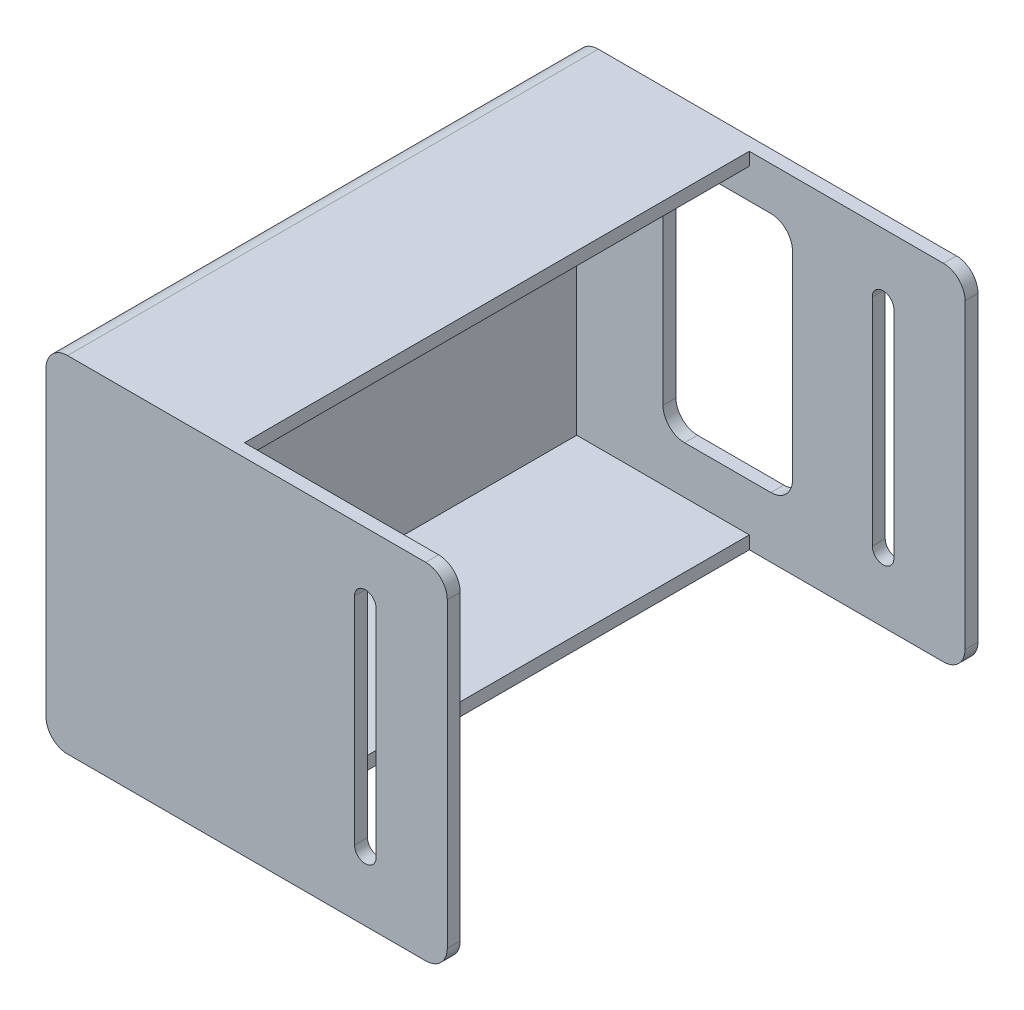
SolidWorks part; units mm, degrees
ref_plane "前基準面" through (0, 0, 0) normal (0, 0, 1) x (1, 0, 0)
ref_plane "上基準面" through (0, 0, 0) normal (0, 1, 0) x (1, 0, 0)
ref_plane "右基準面" through (0, 0, 0) normal (1, 0, 0) x (0, 0, -1)
sketch "草圖1" plane through (0, 0, 0) normal (1, 0, 0) x (0, 0, -1)
  line L1 (-61.5, -40) -> (61.5, -40)
  line L2 (-61.5, -40) -> (-61.5, 40)
  line L3 (-61.5, 40) -> (61.5, 40)
  line L4 (61.5, -40) -> (61.5, 40)
  line L5 (-61.5, -40) -> (61.5, 40) construction
  line L6 (-61.5, 40) -> (61.5, -40) construction
  point P0 (0, 0)
  dimension "D1" = 123
  dimension "D2" = 80
extrude "填料-伸長1" add sketch "草圖1" along normal blind 93
shell "薄殼1" thickness 3
sketch "草圖2" plane through (0, 40, 0) normal (0, 1, 0) x (1, 0, 0)
  line L0 (93, 61.5) -> (93, -61.5) construction
  line L1 (93, 58.5) -> (43, 58.5)
  line L2 (93, 58.5) -> (93, -58.5)
  line L3 (93, -58.5) -> (43, -58.5)
  line L4 (43, 58.5) -> (43, -58.5)
  line L5 (93, -61.5) -> (0, -61.5) construction
  dimension "D1" = 117
  dimension "D2" = 3
  dimension "D3" = 50
extrude "除料-伸長1" cut sketch "草圖2" against normal through all
fillet "圓角1" radius 5 2 edges at (0, 40, 0) (0, -40, 0)
fillet "圓角2" radius 5 4 edges at (93, 40, -60) (93, 40, 60) (93, -40, 60) (93, -40, -60)
sketch "草圖3" plane through (0, 0, -61.5) normal (0, 0, -1) x (-1, 0, 0)
  line L0 (-93, -35) -> (-93, 35) construction
  line L1 (-88, -40) -> (-5, -40) construction
  line L2 (-76.5, -25) -> (-76.5, 25)
  line L3 (-71.5, -25) -> (-71.5, 25)
  arc A0 (-76.5, -25) -> (-71.5, -25) centre (-74, -25) ccw
  arc A1 (-71.5, 25) -> (-76.5, 25) centre (-74, 25) ccw
  dimension "D1" = 5
  dimension "D2" = 19
  dimension "D3" = 15
  dimension "D4" = 50
extrude "除料-伸長2" cut sketch "草圖3" against normal up to next
mirror "鏡射1" about plane through (0, 0, 0) normal (0, 0, 1) of "除料-伸長2"
sketch "草圖5" plane through (0, 0, -61.5) normal (0, 0, -1) x (-1, 0, 0)
  line L0 (-88, 40) -> (-5, 40) construction
  line L1 (-23, 30) -> (-53, 30)
  line L2 (-23, 30) -> (-23, -26)
  line L3 (-23, -26) -> (-53, -26)
  line L4 (-53, 30) -> (-53, -26)
  line L5 (-23, 30) -> (-53, -26) construction
  line L6 (-23, -26) -> (-53, 30) construction
  line L7 (-93, -35) -> (-93, 35) construction
  point P0 (-38, 2)
  dimension "D1" = 30
  dimension "D2" = 56
  dimension "D3" = 10
  dimension "D4" = 40
extrude "除料-伸長4" cut sketch "草圖5" against normal up to next
sketch "草圖6" plane through (0, 0, 0) normal (-1, 0, 0) x (0, 0, 1)
  line L0 (-61.5, 40) -> (61.5, 40) construction
  line L1 (61.5, 35) -> (61.5, -35) construction
  circle A0 centre (41.5, 20) radius 10
  dimension "D1" = 20
  dimension "D2" = 20
  dimension "D3" = 20
extrude "除料-伸長5" cut sketch "草圖6" against normal up to next
fillet "圓角3" radius 5 4 edges at (23, 30, -60) (23, -26, -60) (53, -26, -60) (53, 30, -60)
sketch "草圖7" plane through (0, 0, 0) normal (-1, 0, 0) x (0, 0, 1)
  line L0 (-61.5, 40) -> (61.5, 40) construction
  line L1 (-1.5, 32) -> (3.5, 32)
  line L2 (-1.5, 32) -> (-1.5, 4)
  line L3 (-1.5, 4) -> (3.5, 4)
  line L4 (3.5, 32) -> (3.5, 4)
  line L5 (-1.5, 32) -> (3.5, 4) construction
  line L6 (-1.5, 4) -> (3.5, 32) construction
  line L7 (61.5, 35) -> (61.5, -35) construction
  point P0 (1, 18)
  dimension "D1" = 28
  dimension "D2" = 5
  dimension "D3" = 8
  dimension "D4" = 58
extrude "除料-伸長6" cut sketch "草圖7" against normal up to next
